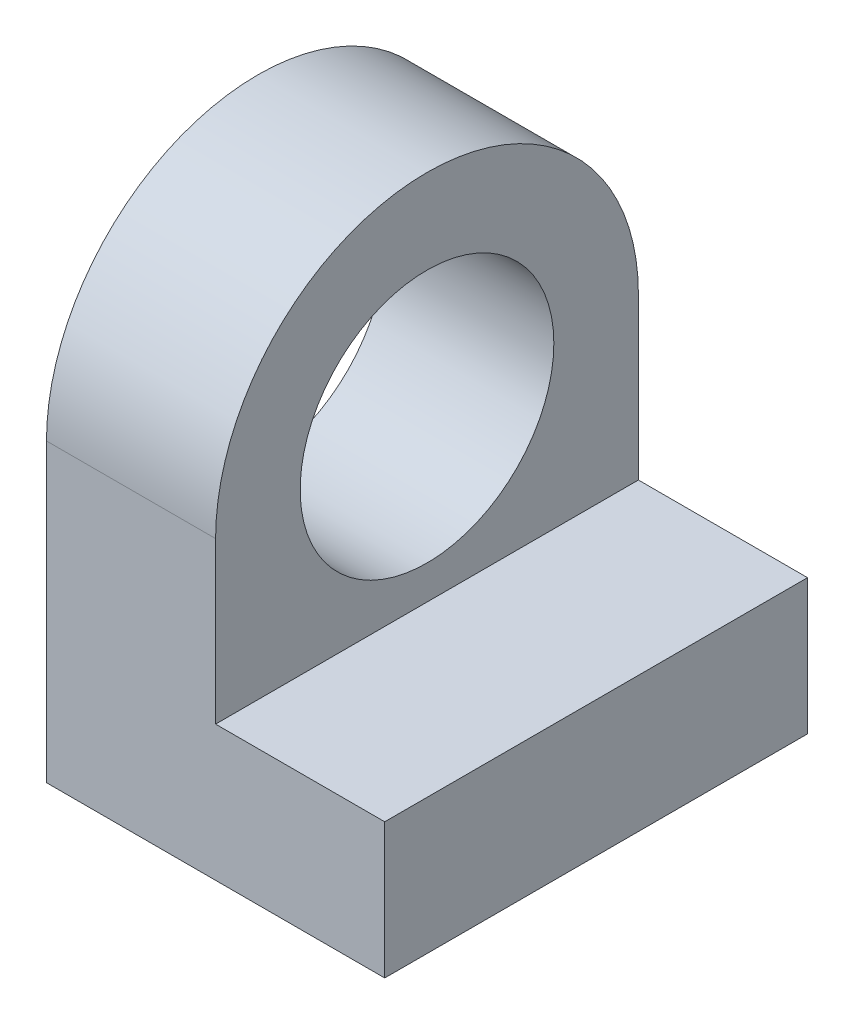
SolidWorks part; units mm, degrees
ref_plane "Alzado" through (0, 0, 0) normal (0, 0, 1) x (1, 0, 0)
ref_plane "Planta" through (0, 0, 0) normal (0, 1, 0) x (1, 0, 0)
ref_plane "Vista lateral" through (0, 0, 0) normal (1, 0, 0) x (0, 0, -1)
sketch "Croquis1" plane through (0, 0, 0) normal (1, 0, 0) x (0, 0, -1)
  line L0 (0, 0) -> (-25, 0)
  line L1 (-25, 0) -> (-25, 17.5)
  line L2 (0, 17.5) -> (0, 0)
  arc A0 (-25, 17.5) -> (0, 17.5) centre (-12.5, 17.5) cw
  circle A1 centre (-12.5, 17.5) radius 7.5
  point P7 (-12.5, 30)
  dimension "D2" = 15
  dimension "D1" = 25
  dimension "D3" = 30
extrude "Saliente-Extruir1" add sketch "Croquis1" along normal blind 10
sketch "Croquis2" plane through (10, 0, 0) normal (1, 0, 0) x (0, 0, -1)
  line L0 (-25, 8) -> (0, 8)
  line L3 (0, 0) -> (0, 17.5)
  line L4 (-25, 17.5) -> (-25, 0)
  line L5 (-25, 0) -> (0, 0)
  line L6 (0, 0) -> (0, 8)
  line L7 (-25, 8) -> (-25, 0)
  line L8 (-25, 0) -> (0, 0)
  arc A1 (0, 17.5) -> (-25, 17.5) centre (-12.5, 17.5) ccw
  dimension "D2" = 8
  dimension "D1" = 0
extrude "Saliente-Extruir2" add sketch "Croquis2" along normal blind 10 contours L6 L0 L7 L8
